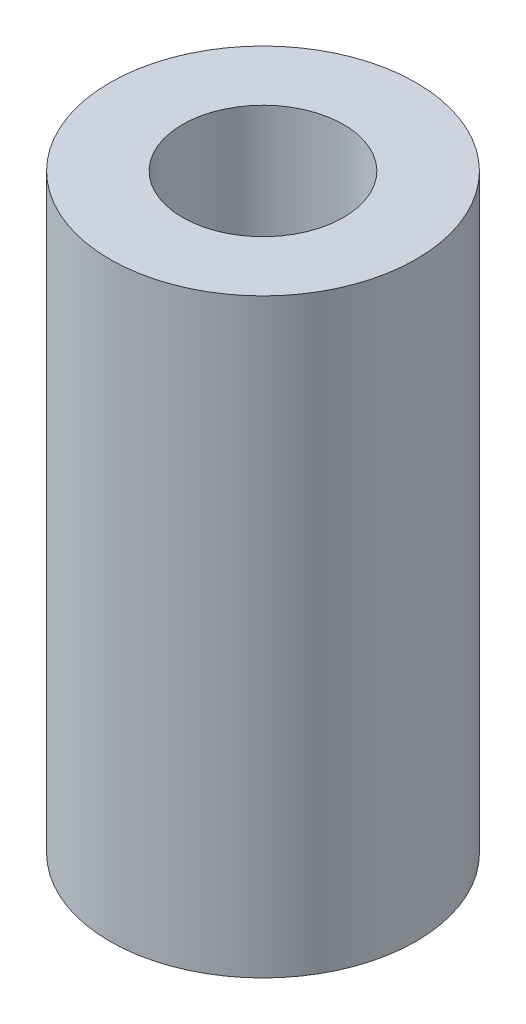
SolidWorks part; units mm, degrees
ref_plane "Front Plane" through (0, 0, 0) normal (0, 0, 1) x (1, 0, 0)
ref_plane "Top Plane" through (0, 0, 0) normal (0, 1, 0) x (1, 0, 0)
ref_plane "Right Plane" through (0, 0, 0) normal (1, 0, 0) x (0, 0, -1)
sketch "Sketch1" plane through (0, 0, 0) normal (0, 1, 0) x (1, 0, 0)
  circle A0 centre (0, 0) radius 1.25
  circle A2 centre (0, 0) radius 2.85
  dimension "D2" = 2.5
  dimension "D1" = 1.6
extrude "Boss-Extrude1" add sketch "Sketch1" along normal blind 11
sketch "Sketch2" plane through (0, 0, 0) normal (0, 1, 0) x (1, 0, 0)
  circle A0 centre (0, 0) radius 1.5
  dimension "D1" = 3
extrude "Cut-Extrude1" cut sketch "Sketch2" along normal blind 6 from offset 6
